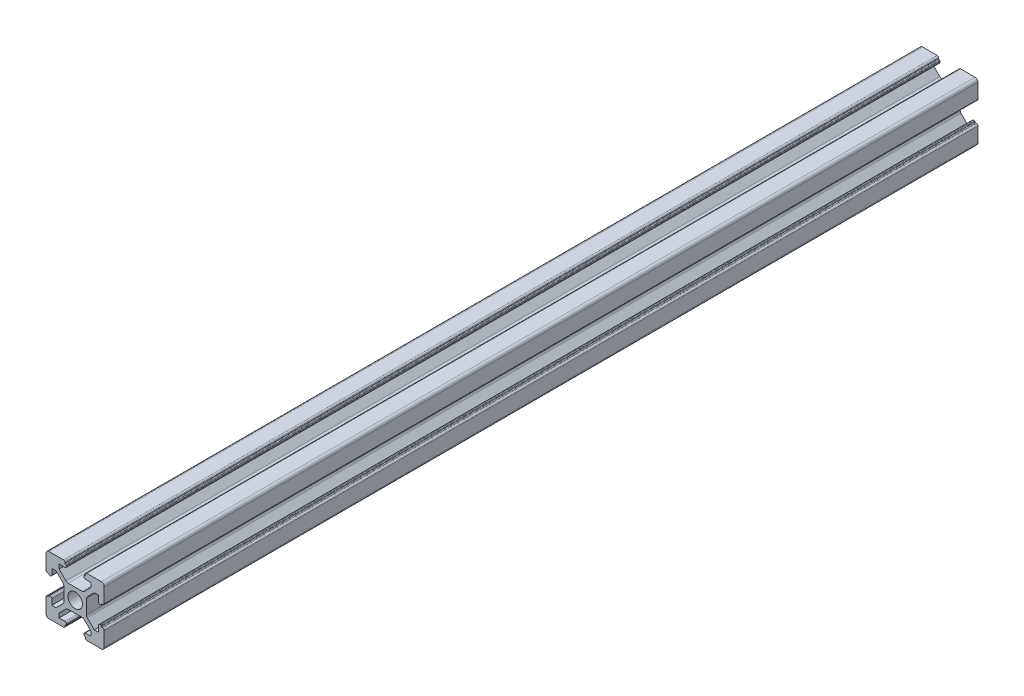
SolidWorks part; units mm, degrees
material "1060 Alloy"
ref_plane "Front Plane" through (0, 0, 0) normal (0, 0, 1) x (1, 0, 0)
ref_plane "Top Plane" through (0, 0, 0) normal (0, 1, 0) x (1, 0, 0)
ref_plane "Right Plane" through (0, 0, 0) normal (1, 0, 0) x (0, 0, -1)
sketch "Sketch2" plane through (0, 0, 0) normal (0, 0, 1) x (1, 0, 0)
  line L0 (3.5, 9.5) -> (3.5, 9.25)
  line L1 (9, -10) -> (-9, -10)
  line L2 (10, -9) -> (10, 9)
  line L3 (9, 10) -> (4, 10)
  line L4 (-10, -9) -> (-10, 9)
  line L5 (10, -10) -> (-10, 10) construction
  line L6 (10, 10) -> (-10, -10) construction
  line L7 (3.25, 9) -> (3.2, 9)
  line L8 (3, 8.8) -> (3, 8.5)
  line L9 (3.5, 8) -> (5.5, 8)
  line L10 (5.5, 8) -> (5.5, 6.5607)
  line L11 (5.5, 6.5607) -> (3.1072, 4.1679)
  line L12 (2.4001, 3.875) -> (0, 3.875)
  line L13 (0, 10) -> (0, 0) construction
  line L14 (0, 10) -> (-9, 10)
  line L15 (10, 10) -> (10, 4)
  line L16 (3.875, 2.4001) -> (3.875, 0)
  line L17 (6.5607, 5.5) -> (4.1679, 3.1072)
  line L18 (8, 5.5) -> (6.5607, 5.5)
  line L19 (8, 3.5) -> (8, 5.5)
  line L20 (8.8, 3) -> (8.5, 3)
  line L21 (9, 3.25) -> (9, 3.2)
  line L22 (9.5, 3.5) -> (9.25, 3.5)
  line L23 (9.5, -3.5) -> (9.25, -3.5)
  line L24 (10, -10) -> (10, -4)
  line L25 (9, -3.25) -> (9, -3.2)
  line L26 (8.8, -3) -> (8.5, -3)
  line L27 (8, -3.5) -> (8, -5.5)
  line L28 (8, -5.5) -> (6.5607, -5.5)
  line L29 (6.5607, -5.5) -> (4.1679, -3.1072)
  line L30 (3.875, -2.4001) -> (3.875, 0)
  line L31 (10, -10) -> (4, -10)
  line L32 (2.4001, -3.875) -> (0, -3.875)
  line L33 (5.5, -6.5607) -> (3.1072, -4.1679)
  line L34 (5.5, -8) -> (5.5, -6.5607)
  line L35 (3.5, -8) -> (5.5, -8)
  line L36 (3, -8.8) -> (3, -8.5)
  line L37 (3.25, -9) -> (3.2, -9)
  line L38 (3.5, -9.5) -> (3.5, -9.25)
  line L39 (10, 0) -> (0, 0) construction
  line L40 (-3.5, -9.5) -> (-3.5, -9.25)
  line L41 (-10, -10) -> (-4, -10)
  line L42 (-3.25, -9) -> (-3.2, -9)
  line L43 (-3, -8.8) -> (-3, -8.5)
  line L44 (-3.5, -8) -> (-5.5, -8)
  line L45 (-5.5, -8) -> (-5.5, -6.5607)
  line L46 (-5.5, -6.5607) -> (-3.1072, -4.1679)
  line L47 (-2.4001, -3.875) -> (0, -3.875)
  line L48 (-10, -10) -> (-10, -4)
  line L49 (-3.875, -2.4001) -> (-3.875, 0)
  line L50 (-6.5607, -5.5) -> (-4.1679, -3.1072)
  line L51 (-8, -5.5) -> (-6.5607, -5.5)
  line L52 (-8, -3.5) -> (-8, -5.5)
  line L53 (-8.8, -3) -> (-8.5, -3)
  line L54 (-9, -3.25) -> (-9, -3.2)
  line L55 (-9.5, -3.5) -> (-9.25, -3.5)
  line L56 (0, -10) -> (0, 0) construction
  line L57 (-9.5, 3.5) -> (-9.25, 3.5)
  line L58 (-10, 10) -> (-10, 4)
  line L59 (-9, 3.25) -> (-9, 3.2)
  line L60 (-8.8, 3) -> (-8.5, 3)
  line L61 (-8, 3.5) -> (-8, 5.5)
  line L62 (-8, 5.5) -> (-6.5607, 5.5)
  line L63 (-6.5607, 5.5) -> (-4.1679, 3.1072)
  line L64 (-3.875, 2.4001) -> (-3.875, 0)
  line L65 (-10, 10) -> (-4, 10)
  line L66 (-2.4001, 3.875) -> (0, 3.875)
  line L67 (-5.5, 6.5607) -> (-3.1072, 4.1679)
  line L68 (-5.5, 8) -> (-5.5, 6.5607)
  line L69 (-3.5, 8) -> (-5.5, 8)
  line L70 (-3, 8.8) -> (-3, 8.5)
  line L71 (-3.25, 9) -> (-3.2, 9)
  line L72 (-3.5, 9.5) -> (-3.5, 9.25)
  line L73 (-10, 0) -> (0, 0) construction
  arc A0 (3.5, 9.5) -> (4, 10) centre (4, 9.5) cw
  arc A1 (3.25, 9) -> (3.5, 9.25) centre (3.25, 9.25) ccw
  arc A2 (3.2, 9) -> (3, 8.8) centre (3.2, 8.8) ccw
  arc A3 (3.5, 8) -> (3, 8.5) centre (3.5, 8.5) cw
  arc A4 (3.1072, 4.1679) -> (2.4001, 3.875) centre (2.4001, 4.875) cw
  arc A5 (4.1679, 3.1072) -> (3.875, 2.4001) centre (4.875, 2.4001) ccw
  arc A6 (8, 3.5) -> (8.5, 3) centre (8.5, 3.5) ccw
  arc A7 (9, 3.2) -> (8.8, 3) centre (8.8, 3.2) cw
  arc A8 (9, 3.25) -> (9.25, 3.5) centre (9.25, 3.25) cw
  arc A9 (9.5, 3.5) -> (10, 4) centre (9.5, 4) ccw
  arc A10 (9.5, -3.5) -> (10, -4) centre (9.5, -4) cw
  arc A11 (9, -3.25) -> (9.25, -3.5) centre (9.25, -3.25) ccw
  arc A12 (9, -3.2) -> (8.8, -3) centre (8.8, -3.2) ccw
  arc A13 (8, -3.5) -> (8.5, -3) centre (8.5, -3.5) cw
  arc A14 (4.1679, -3.1072) -> (3.875, -2.4001) centre (4.875, -2.4001) cw
  arc A15 (3.1072, -4.1679) -> (2.4001, -3.875) centre (2.4001, -4.875) ccw
  arc A16 (3.5, -8) -> (3, -8.5) centre (3.5, -8.5) ccw
  arc A17 (3.2, -9) -> (3, -8.8) centre (3.2, -8.8) cw
  arc A18 (3.25, -9) -> (3.5, -9.25) centre (3.25, -9.25) cw
  arc A19 (3.5, -9.5) -> (4, -10) centre (4, -9.5) ccw
  arc A20 (-3.5, -9.5) -> (-4, -10) centre (-4, -9.5) cw
  arc A21 (-3.25, -9) -> (-3.5, -9.25) centre (-3.25, -9.25) ccw
  arc A22 (-3.2, -9) -> (-3, -8.8) centre (-3.2, -8.8) ccw
  arc A23 (-3.5, -8) -> (-3, -8.5) centre (-3.5, -8.5) cw
  arc A24 (-3.1072, -4.1679) -> (-2.4001, -3.875) centre (-2.4001, -4.875) cw
  arc A25 (-4.1679, -3.1072) -> (-3.875, -2.4001) centre (-4.875, -2.4001) ccw
  arc A26 (-8, -3.5) -> (-8.5, -3) centre (-8.5, -3.5) ccw
  arc A27 (-9, -3.2) -> (-8.8, -3) centre (-8.8, -3.2) cw
  arc A28 (-9, -3.25) -> (-9.25, -3.5) centre (-9.25, -3.25) cw
  arc A29 (-9.5, -3.5) -> (-10, -4) centre (-9.5, -4) ccw
  arc A30 (-9.5, 3.5) -> (-10, 4) centre (-9.5, 4) cw
  arc A31 (-9, 3.25) -> (-9.25, 3.5) centre (-9.25, 3.25) ccw
  arc A32 (-9, 3.2) -> (-8.8, 3) centre (-8.8, 3.2) ccw
  arc A33 (-8, 3.5) -> (-8.5, 3) centre (-8.5, 3.5) cw
  arc A34 (-4.1679, 3.1072) -> (-3.875, 2.4001) centre (-4.875, 2.4001) cw
  arc A35 (-3.1072, 4.1679) -> (-2.4001, 3.875) centre (-2.4001, 4.875) ccw
  arc A36 (-3.5, 8) -> (-3, 8.5) centre (-3.5, 8.5) ccw
  arc A37 (-3.2, 9) -> (-3, 8.8) centre (-3.2, 8.8) cw
  arc A38 (-3.25, 9) -> (-3.5, 9.25) centre (-3.25, 9.25) cw
  arc A39 (-3.5, 9.5) -> (-4, 10) centre (-4, 9.5) ccw
  circle A40 centre (0, 0) radius 2.5
  arc A41 (-10, 9) -> (-9, 10) centre (-9, 9) cw
  arc A42 (-10, -9) -> (-9, -10) centre (-9, -9) ccw
  arc A43 (9, -10) -> (10, -9) centre (9, -9) ccw
  arc A44 (10, 9) -> (9, 10) centre (9, 9) ccw
  point P0 (0, 0)
  point P17 (0, 0)
  point P23 (3.5, 10)
  point P26 (3.5, 9)
  point P52 (9, 3.5)
  point P53 (10, 3.5)
  point P90 (3.5, -9)
  point P91 (3.5, -10)
  point P92 (0, 0)
  point P131 (-9, -3.5)
  point P132 (-10, -3.5)
  point P133 (0, 0)
  point P172 (-3.5, 9)
  point P173 (-3.5, 10)
  point P174 (0, 0)
  dimension "D10" = 0.5
  dimension "D11" = 0.25
  dimension "D12" = 0.2
  dimension "D13" = 0.5
  dimension "D14" = 1
  dimension "D16" = 5
  dimension "D17" = 1
  dimension "D1" = 20
  dimension "D2" = 20
  dimension "D3" = 1.5
  dimension "D4" = 3.875
  dimension "D5" = 11
  dimension "D6" = 7
  dimension "D7" = 6
  dimension "D8" = 2
  dimension "D9" = 1
  dimension "D15" = 4
extrude "Boss-Extrude1" add sketch "Sketch2" along normal blind 300 contours L72 A39 L14 L4 A30 L57 A31 L59 A32 L60 A33 L61 L62 L63 A34 L64 L49 A25 L50 L51 L52 A26 L53 A27 L54 A28 L55 A29 L1 A20 L40 A21 L42 A22 L43 A23 L44 L45 L46 A24 L47 L32 A15 L33 L34 L35 A16 L36 A17 L37
sketch "Sketch3" plane through (0, 0, 300) normal (0, 0, 1) x (1, 0, 0)
  line L60 (10, 4) -> (10, 9)
  line L61 (9, 10) -> (4, 10)
  line L62 (3.5, 9.5) -> (3.5, 9.25)
  line L63 (3.25, 9) -> (3.2, 9)
  line L64 (3, 8.8) -> (3, 8.5)
  line L65 (3.5, 8) -> (5.5, 8)
  line L66 (5.5, 8) -> (5.5, 6.5607)
  line L67 (5.5, 6.5607) -> (3.1072, 4.1679)
  line L68 (2.4001, 3.875) -> (-2.4001, 3.875)
  line L69 (-3.1072, 4.1679) -> (-5.5, 6.5607)
  line L70 (-5.5, 6.5607) -> (-5.5, 8)
  line L71 (-5.5, 8) -> (-3.5, 8)
  line L72 (-3, 8.5) -> (-3, 8.8)
  line L73 (-3.2, 9) -> (-3.25, 9)
  line L74 (-3.5, 9.25) -> (-3.5, 9.5)
  line L75 (-4, 10) -> (-9, 10)
  line L76 (-10, 9) -> (-10, 4)
  line L77 (-9.5, 3.5) -> (-9.25, 3.5)
  line L78 (-9, 3.25) -> (-9, 3.2)
  line L79 (-8.8, 3) -> (-8.5, 3)
  line L80 (-8, 3.5) -> (-8, 5.5)
  line L81 (-8, 5.5) -> (-6.5607, 5.5)
  line L82 (-6.5607, 5.5) -> (-4.1679, 3.1072)
  line L83 (-3.875, 2.4001) -> (-3.875, -2.4001)
  line L84 (-4.1679, -3.1072) -> (-6.5607, -5.5)
  line L85 (-6.5607, -5.5) -> (-8, -5.5)
  line L86 (-8, -5.5) -> (-8, -3.5)
  line L87 (-8.5, -3) -> (-8.8, -3)
  line L88 (-9, -3.2) -> (-9, -3.25)
  line L89 (-9.25, -3.5) -> (-9.5, -3.5)
  line L90 (-10, -4) -> (-10, -9)
  line L91 (-9, -10) -> (-4, -10)
  line L92 (-3.5, -9.5) -> (-3.5, -9.25)
  line L93 (-3.25, -9) -> (-3.2, -9)
  line L94 (-3, -8.8) -> (-3, -8.5)
  line L95 (-3.5, -8) -> (-5.5, -8)
  line L96 (-5.5, -8) -> (-5.5, -6.5607)
  line L97 (-5.5, -6.5607) -> (-3.1072, -4.1679)
  line L98 (-2.4001, -3.875) -> (2.4001, -3.875)
  line L99 (3.1072, -4.1679) -> (5.5, -6.5607)
  line L100 (5.5, -6.5607) -> (5.5, -8)
  line L101 (5.5, -8) -> (3.5, -8)
  line L102 (3, -8.5) -> (3, -8.8)
  line L103 (3.2, -9) -> (3.25, -9)
  line L104 (3.5, -9.25) -> (3.5, -9.5)
  line L105 (4, -10) -> (9, -10)
  line L106 (10, -9) -> (10, -4)
  line L107 (9.5, -3.5) -> (9.25, -3.5)
  line L108 (9, -3.25) -> (9, -3.2)
  line L109 (8.8, -3) -> (8.5, -3)
  line L110 (8, -3.5) -> (8, -5.5)
  line L111 (8, -5.5) -> (6.5607, -5.5)
  line L112 (6.5607, -5.5) -> (4.1679, -3.1072)
  line L113 (3.875, -2.4001) -> (3.875, 2.4001)
  line L114 (4.1679, 3.1072) -> (6.5607, 5.5)
  line L115 (6.5607, 5.5) -> (8, 5.5)
  line L116 (8, 5.5) -> (8, 3.5)
  line L117 (8.5, 3) -> (8.8, 3)
  line L118 (9, 3.2) -> (9, 3.25)
  line L119 (9.25, 3.5) -> (9.5, 3.5)
  line L120 (10, 4) -> (10, 9)
  line L121 (9, 10) -> (4, 10)
  line L122 (3.5, 9.5) -> (3.5, 9.25)
  line L123 (3.25, 9) -> (3.2, 9)
  line L124 (3, 8.8) -> (3, 8.5)
  line L125 (3.5, 8) -> (5.5, 8)
  line L126 (5.5, 8) -> (5.5, 6.5607)
  line L127 (5.5, 6.5607) -> (3.1072, 4.1679)
  line L128 (2.4001, 3.875) -> (-2.4001, 3.875)
  line L129 (-3.1072, 4.1679) -> (-5.5, 6.5607)
  line L130 (-5.5, 6.5607) -> (-5.5, 8)
  line L131 (-5.5, 8) -> (-3.5, 8)
  line L132 (-3, 8.5) -> (-3, 8.8)
  line L133 (-3.2, 9) -> (-3.25, 9)
  line L134 (-3.5, 9.25) -> (-3.5, 9.5)
  line L135 (-4, 10) -> (-9, 10)
  line L136 (-10, 9) -> (-10, 4)
  line L137 (-9.5, 3.5) -> (-9.25, 3.5)
  line L138 (-9, 3.25) -> (-9, 3.2)
  line L139 (-8.8, 3) -> (-8.5, 3)
  line L140 (-8, 3.5) -> (-8, 5.5)
  line L141 (-8, 5.5) -> (-6.5607, 5.5)
  line L142 (-6.5607, 5.5) -> (-4.1679, 3.1072)
  line L143 (-3.875, 2.4001) -> (-3.875, -2.4001)
  line L144 (-4.1679, -3.1072) -> (-6.5607, -5.5)
  line L145 (-6.5607, -5.5) -> (-8, -5.5)
  line L146 (-8, -5.5) -> (-8, -3.5)
  line L147 (-8.5, -3) -> (-8.8, -3)
  line L148 (-9, -3.2) -> (-9, -3.25)
  line L149 (-9.25, -3.5) -> (-9.5, -3.5)
  line L150 (-10, -4) -> (-10, -9)
  line L151 (-9, -10) -> (-4, -10)
  line L152 (-3.5, -9.5) -> (-3.5, -9.25)
  line L153 (-3.25, -9) -> (-3.2, -9)
  line L154 (-3, -8.8) -> (-3, -8.5)
  line L155 (-3.5, -8) -> (-5.5, -8)
  line L156 (-5.5, -8) -> (-5.5, -6.5607)
  line L157 (-5.5, -6.5607) -> (-3.1072, -4.1679)
  line L158 (-2.4001, -3.875) -> (2.4001, -3.875)
  line L159 (3.1072, -4.1679) -> (5.5, -6.5607)
  line L160 (5.5, -6.5607) -> (5.5, -8)
  line L161 (5.5, -8) -> (3.5, -8)
  line L162 (3, -8.5) -> (3, -8.8)
  line L163 (3.2, -9) -> (3.25, -9)
  line L164 (3.5, -9.25) -> (3.5, -9.5)
  line L165 (4, -10) -> (9, -10)
  line L166 (10, -9) -> (10, -4)
  line L167 (9.5, -3.5) -> (9.25, -3.5)
  line L168 (9, -3.25) -> (9, -3.2)
  line L169 (8.8, -3) -> (8.5, -3)
  line L170 (8, -3.5) -> (8, -5.5)
  line L171 (8, -5.5) -> (6.5607, -5.5)
  line L172 (6.5607, -5.5) -> (4.1679, -3.1072)
  line L173 (3.875, -2.4001) -> (3.875, 2.4001)
  line L174 (4.1679, 3.1072) -> (6.5607, 5.5)
  line L175 (6.5607, 5.5) -> (8, 5.5)
  line L176 (8, 5.5) -> (8, 3.5)
  line L177 (8.5, 3) -> (8.8, 3)
  line L178 (9, 3.2) -> (9, 3.25)
  line L179 (9.25, 3.5) -> (9.5, 3.5)
  arc A44 (10, 9) -> (9, 10) centre (9, 9) ccw
  arc A45 (4, 10) -> (3.5, 9.5) centre (4, 9.5) ccw
  arc A46 (3.25, 9) -> (3.5, 9.25) centre (3.25, 9.25) ccw
  arc A47 (3.2, 9) -> (3, 8.8) centre (3.2, 8.8) ccw
  arc A48 (3, 8.5) -> (3.5, 8) centre (3.5, 8.5) ccw
  arc A49 (2.4001, 3.875) -> (3.1072, 4.1679) centre (2.4001, 4.875) ccw
  arc A50 (-3.1072, 4.1679) -> (-2.4001, 3.875) centre (-2.4001, 4.875) ccw
  arc A51 (-3.5, 8) -> (-3, 8.5) centre (-3.5, 8.5) ccw
  arc A52 (-3, 8.8) -> (-3.2, 9) centre (-3.2, 8.8) ccw
  arc A53 (-3.5, 9.25) -> (-3.25, 9) centre (-3.25, 9.25) ccw
  arc A54 (-3.5, 9.5) -> (-4, 10) centre (-4, 9.5) ccw
  arc A55 (-9, 10) -> (-10, 9) centre (-9, 9) ccw
  arc A56 (-10, 4) -> (-9.5, 3.5) centre (-9.5, 4) ccw
  arc A57 (-9, 3.25) -> (-9.25, 3.5) centre (-9.25, 3.25) ccw
  arc A58 (-9, 3.2) -> (-8.8, 3) centre (-8.8, 3.2) ccw
  arc A59 (-8.5, 3) -> (-8, 3.5) centre (-8.5, 3.5) ccw
  arc A60 (-3.875, 2.4001) -> (-4.1679, 3.1072) centre (-4.875, 2.4001) ccw
  arc A61 (-4.1679, -3.1072) -> (-3.875, -2.4001) centre (-4.875, -2.4001) ccw
  arc A62 (-8, -3.5) -> (-8.5, -3) centre (-8.5, -3.5) ccw
  arc A63 (-8.8, -3) -> (-9, -3.2) centre (-8.8, -3.2) ccw
  arc A64 (-9.25, -3.5) -> (-9, -3.25) centre (-9.25, -3.25) ccw
  arc A65 (-9.5, -3.5) -> (-10, -4) centre (-9.5, -4) ccw
  arc A66 (-10, -9) -> (-9, -10) centre (-9, -9) ccw
  arc A67 (-4, -10) -> (-3.5, -9.5) centre (-4, -9.5) ccw
  arc A68 (-3.25, -9) -> (-3.5, -9.25) centre (-3.25, -9.25) ccw
  arc A69 (-3.2, -9) -> (-3, -8.8) centre (-3.2, -8.8) ccw
  arc A70 (-3, -8.5) -> (-3.5, -8) centre (-3.5, -8.5) ccw
  arc A71 (-2.4001, -3.875) -> (-3.1072, -4.1679) centre (-2.4001, -4.875) ccw
  arc A72 (3.1072, -4.1679) -> (2.4001, -3.875) centre (2.4001, -4.875) ccw
  arc A73 (3.5, -8) -> (3, -8.5) centre (3.5, -8.5) ccw
  arc A74 (3, -8.8) -> (3.2, -9) centre (3.2, -8.8) ccw
  arc A75 (3.5, -9.25) -> (3.25, -9) centre (3.25, -9.25) ccw
  arc A76 (3.5, -9.5) -> (4, -10) centre (4, -9.5) ccw
  arc A77 (9, -10) -> (10, -9) centre (9, -9) ccw
  arc A78 (10, -4) -> (9.5, -3.5) centre (9.5, -4) ccw
  arc A79 (9, -3.25) -> (9.25, -3.5) centre (9.25, -3.25) ccw
  arc A80 (9, -3.2) -> (8.8, -3) centre (8.8, -3.2) ccw
  arc A81 (8.5, -3) -> (8, -3.5) centre (8.5, -3.5) ccw
  arc A82 (3.875, -2.4001) -> (4.1679, -3.1072) centre (4.875, -2.4001) ccw
  arc A83 (4.1679, 3.1072) -> (3.875, 2.4001) centre (4.875, 2.4001) ccw
  arc A84 (8, 3.5) -> (8.5, 3) centre (8.5, 3.5) ccw
  arc A85 (8.8, 3) -> (9, 3.2) centre (8.8, 3.2) ccw
  arc A86 (9.25, 3.5) -> (9, 3.25) centre (9.25, 3.25) ccw
  arc A87 (9.5, 3.5) -> (10, 4) centre (9.5, 4) ccw
  arc A88 (10, 9) -> (9, 10) centre (9, 9) ccw
  arc A89 (4, 10) -> (3.5, 9.5) centre (4, 9.5) ccw
  arc A90 (3.25, 9) -> (3.5, 9.25) centre (3.25, 9.25) ccw
  arc A91 (3.2, 9) -> (3, 8.8) centre (3.2, 8.8) ccw
  arc A92 (3, 8.5) -> (3.5, 8) centre (3.5, 8.5) ccw
  arc A93 (2.4001, 3.875) -> (3.1072, 4.1679) centre (2.4001, 4.875) ccw
  arc A94 (-3.1072, 4.1679) -> (-2.4001, 3.875) centre (-2.4001, 4.875) ccw
  arc A95 (-3.5, 8) -> (-3, 8.5) centre (-3.5, 8.5) ccw
  arc A96 (-3, 8.8) -> (-3.2, 9) centre (-3.2, 8.8) ccw
  arc A97 (-3.5, 9.25) -> (-3.25, 9) centre (-3.25, 9.25) ccw
  arc A98 (-3.5, 9.5) -> (-4, 10) centre (-4, 9.5) ccw
  arc A99 (-9, 10) -> (-10, 9) centre (-9, 9) ccw
  arc A100 (-10, 4) -> (-9.5, 3.5) centre (-9.5, 4) ccw
  arc A101 (-9, 3.25) -> (-9.25, 3.5) centre (-9.25, 3.25) ccw
  arc A102 (-9, 3.2) -> (-8.8, 3) centre (-8.8, 3.2) ccw
  arc A103 (-8.5, 3) -> (-8, 3.5) centre (-8.5, 3.5) ccw
  arc A104 (-3.875, 2.4001) -> (-4.1679, 3.1072) centre (-4.875, 2.4001) ccw
  arc A105 (-4.1679, -3.1072) -> (-3.875, -2.4001) centre (-4.875, -2.4001) ccw
  arc A106 (-8, -3.5) -> (-8.5, -3) centre (-8.5, -3.5) ccw
  arc A107 (-8.8, -3) -> (-9, -3.2) centre (-8.8, -3.2) ccw
  arc A108 (-9.25, -3.5) -> (-9, -3.25) centre (-9.25, -3.25) ccw
  arc A109 (-9.5, -3.5) -> (-10, -4) centre (-9.5, -4) ccw
  arc A110 (-10, -9) -> (-9, -10) centre (-9, -9) ccw
  arc A111 (-4, -10) -> (-3.5, -9.5) centre (-4, -9.5) ccw
  arc A112 (-3.25, -9) -> (-3.5, -9.25) centre (-3.25, -9.25) ccw
  arc A113 (-3.2, -9) -> (-3, -8.8) centre (-3.2, -8.8) ccw
  arc A114 (-3, -8.5) -> (-3.5, -8) centre (-3.5, -8.5) ccw
  arc A115 (-2.4001, -3.875) -> (-3.1072, -4.1679) centre (-2.4001, -4.875) ccw
  arc A116 (3.1072, -4.1679) -> (2.4001, -3.875) centre (2.4001, -4.875) ccw
  arc A117 (3.5, -8) -> (3, -8.5) centre (3.5, -8.5) ccw
  arc A118 (3, -8.8) -> (3.2, -9) centre (3.2, -8.8) ccw
  arc A119 (3.5, -9.25) -> (3.25, -9) centre (3.25, -9.25) ccw
  arc A120 (3.5, -9.5) -> (4, -10) centre (4, -9.5) ccw
  arc A121 (9, -10) -> (10, -9) centre (9, -9) ccw
  arc A122 (10, -4) -> (9.5, -3.5) centre (9.5, -4) ccw
  arc A123 (9, -3.25) -> (9.25, -3.5) centre (9.25, -3.25) ccw
  arc A124 (9, -3.2) -> (8.8, -3) centre (8.8, -3.2) ccw
  arc A125 (8.5, -3) -> (8, -3.5) centre (8.5, -3.5) ccw
  arc A126 (3.875, -2.4001) -> (4.1679, -3.1072) centre (4.875, -2.4001) ccw
  arc A127 (4.1679, 3.1072) -> (3.875, 2.4001) centre (4.875, 2.4001) ccw
  arc A128 (8, 3.5) -> (8.5, 3) centre (8.5, 3.5) ccw
  arc A129 (8.8, 3) -> (9, 3.2) centre (8.8, 3.2) ccw
  arc A130 (9.25, 3.5) -> (9, 3.25) centre (9.25, 3.25) ccw
  arc A131 (9.5, 3.5) -> (10, 4) centre (9.5, 4) ccw
  dimension "D1" = 0
ref_plane "Plane1" through (0, 0, 150) normal (0, 0, -1) x (-1, 0, 0)
sketch "Sketch4" plane through (0, 0, 300) normal (0, 0, 1) x (1, 0, 0)
  point P0 (0, 0)
equation "\"Length@Boss-Extrude1\" = 300.00mm"
equation "\"Length\"= 150"
